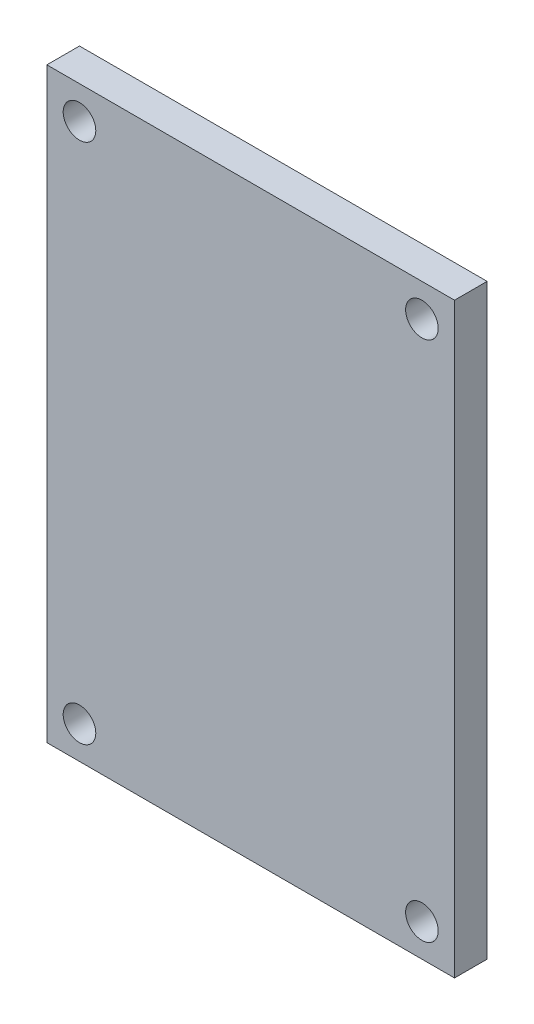
SolidWorks part; units mm, degrees
ref_plane "Front Plane" through (0, 0, 0) normal (0, 0, 1) x (1, 0, 0)
ref_plane "Top Plane" through (0, 0, 0) normal (0, 1, 0) x (1, 0, 0)
ref_plane "Right Plane" through (0, 0, 0) normal (1, 0, 0) x (0, 0, -1)
sketch "Sketch1" plane through (0, 0, 0) normal (0, 0, 1) x (1, 0, 0)
  line L0 (14.0895, 0) -> (-19.7613, 0) construction
  line L1 (12.5, 18) -> (-12.5, 18)
  line L2 (12.5, 18) -> (12.5, -18)
  line L3 (12.5, -18) -> (-12.5, -18)
  line L4 (-12.5, 18) -> (-12.5, -18)
  line L5 (-12.5, -18) -> (-12.5, 0) construction
  line L6 (-12.5, 0) -> (-12.5, 18) construction
  line L7 (0, -20.2309) -> (0, 19.6763) construction
  circle A4 centre (-10.5, -16) radius 1
  circle A5 centre (-10.5, 16) radius 1
  circle A6 centre (10.5, 16) radius 1
  circle A7 centre (10.5, -16) radius 1
  point P8 (-12.5, 0)
  point P14 (0, -18)
  dimension "D1" = 36
  dimension "D2" = 25
extrude "Boss-Extrude1" add sketch "Sketch1" along normal blind 2
